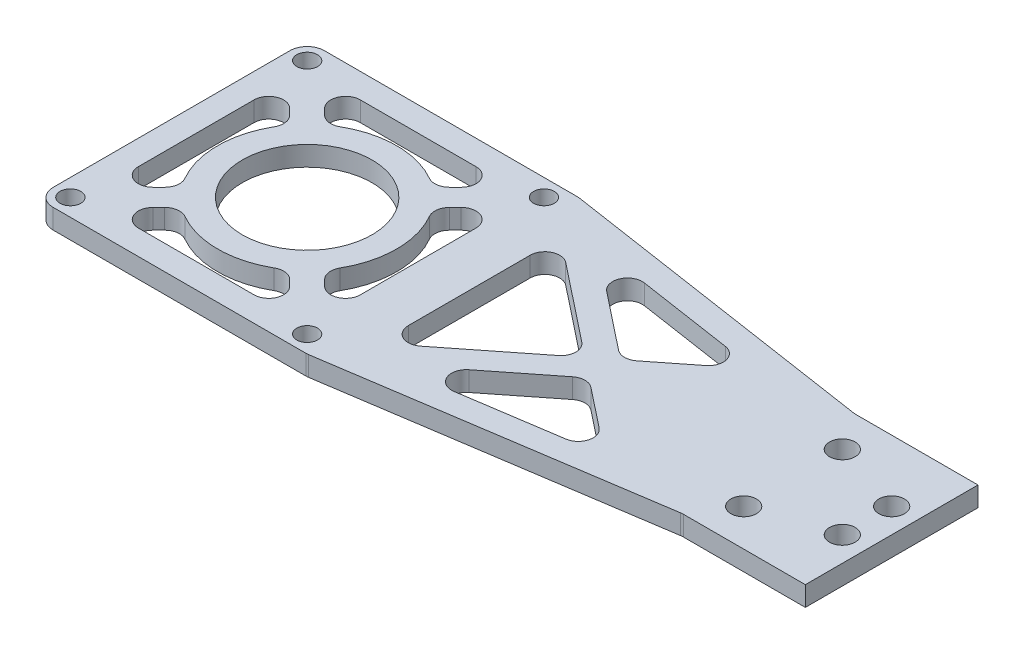
SolidWorks part; units mm, degrees
material "1060 合金"
ref_plane "前视基准面" through (0, 0, 0) normal (0, 0, 1) x (1, 0, 0)
ref_plane "上视基准面" through (0, 0, 0) normal (0, 1, 0) x (1, 0, 0)
ref_plane "右视基准面" through (0, 0, 0) normal (1, 0, 0) x (0, 0, -1)
sketch "草图1" plane through (0, 0, 0) normal (0, 1, 0) x (1, 0, 0)
  line L0 (0, 0) -> (7.5, 0)
  line L1 (-7.5, -10) -> (7.5, -10)
  line L2 (-7.5, -10) -> (-7.5, 10)
  line L3 (-7.5, 10) -> (7.5, 10)
  line L4 (7.5, -10) -> (7.5, 10)
  line L5 (-7.5, -10) -> (7.5, 10) construction
  line L6 (-7.5, 10) -> (7.5, -10) construction
  line L7 (7.5, -5) -> (7.5, 5)
  line L9 (12.5, 17.5) -> (-12.5, 17.5)
  line L10 (12.5, 17.5) -> (12.5, -17.5)
  line L11 (12.5, -17.5) -> (-12.5, -17.5)
  line L12 (-12.5, 17.5) -> (-12.5, -17.5)
  line L13 (12.5, 17.5) -> (-12.5, -17.5) construction
  line L14 (12.5, -17.5) -> (-12.5, 17.5) construction
  circle A0 centre (7.5, 5) radius 2.6
  circle A1 centre (7.5, -5) radius 2.6
  circle A2 centre (-7.5, -10) radius 2.6
  circle A3 centre (-7.5, 10) radius 2.6
  point P0 (0, 0)
  point P11 (7.5, 0)
  dimension "D3" = 10
  dimension "D4" = 5.2
  dimension "D5" = 5.2
  dimension "D6" = 5.2
  dimension "D7" = 5.2
  dimension "D1" = 20
  dimension "D2" = 15
  dimension "D8" = 7.5
  dimension "D9" = 5
extrude "凸台-拉伸1" add sketch "草图1" along normal blind 4
sketch "草图2" plane through (0, 4, 0) normal (0, 1, 0) x (1, 0, 0)
  line L0 (-22.5, 0) -> (0, 0)
  line L1 (-133.482, 27.5) -> (-78.482, 27.5)
  line L2 (-133.482, 27.5) -> (-133.482, -27.5)
  line L3 (-133.482, -27.5) -> (-78.482, -27.5)
  line L4 (-78.482, 27.5) -> (-78.482, -27.5)
  line L5 (-133.482, 27.5) -> (-78.482, -27.5) construction
  line L6 (-133.482, -27.5) -> (-78.482, 27.5) construction
  line L7 (-12.5, 17.5) -> (-12.5, -17.5) construction
  line L8 (-105.982, 0) -> (-22.5, 0)
  line L9 (-78.482, 27.5) -> (-12.5, 17.5)
  line L10 (-12.5, 17.5) -> (-12.5, -17.5)
  line L11 (-12.5, -17.5) -> (-78.482, -27.5)
  circle A0 centre (-22.5, 0) radius 6.0415
  circle A2 centre (-105.982, 0) radius 27.5
  circle A3 centre (-7.5, -10) radius 2.6 construction
  dimension "D1" = 12.0829
  dimension "D2" = 83.482
  dimension "D3" = 15
  dimension "D4" = 55
  dimension "D7" = 90
  dimension "D5" = 55
  dimension "D6" = 55
  dimension "D8" = 180
extrude "凸台-拉伸2" add sketch "草图2" against normal blind 4 separate body
combine bodies "组合1" operation type add bodies to combine 106 107
fillet "圆角1" radius 3.5 6 edges at (-12.5, 2, -17.5) (-78.482, 2, -27.5) (-133.482, 2, 27.5) (-78.482, 2, 27.5) (-12.5, 2, 17.5) (-133.482, 2, -27.5)
sketch "草图3" plane through (0, 4, 0) normal (0, 1, 0) x (1, 0, 0)
  line L0 (-129.982, 24) -> (-105.982, 0)
  line L1 (-105.982, 0) -> (-129.982, -24)
  line L2 (-133.482, 24) -> (-133.482, -24) construction
  circle A0 centre (-105.982, 0) radius 13.15
  dimension "D1" = 90
  dimension "D4" = 26.3
  dimension "D2" = 45
  dimension "D3" = 0
extrude "切除-拉伸1" cut sketch "草图3" against normal blind 10 contours L0 A0 L1 | L1 A0 L0
sketch "草图4" plane through (0, 4, 0) normal (0, 1, 0) x (1, 0, 0)
  line L0 (-93.6076, 12.3744) -> (-105.982, 0)
  line L2 (-133.482, 24) -> (-133.482, -24) construction
  line L4 (-129.982, 24) -> (-81.982, 24)
  line L5 (-129.982, 24) -> (-129.982, -24)
  line L6 (-129.982, -24) -> (-81.982, -24)
  line L7 (-81.982, 24) -> (-81.982, -24)
  line L8 (-129.982, 24) -> (-81.982, -24) construction
  line L9 (-129.982, -24) -> (-81.982, 24) construction
  circle A0 centre (-105.982, 0) radius 17.5
  circle A1 centre (-93.6076, 12.3744) radius 2.1
  circle A2 centre (-81.982, 24) radius 2.1
  dimension "D1" = 35
  dimension "D2" = 4.2
  dimension "D6" = 4.2
  dimension "D3" = 45
  dimension "D4" = 48
  dimension "D5" = 48
extrude "切除-拉伸2" cut sketch "草图4" against normal blind 10 contours L4 A2 L7 | L7 A2 L4
pattern_circular "阵列(圆周)1" count 4 over 360 about axis through (-105.982, 0, 0) along (0, 1, 0) of "切除-拉伸2"
sketch "草图5" plane through (0, 4, 0) normal (0, 1, 0) x (1, 0, 0)
  line L0 (-129.982, 24) -> (-81.982, -24)
  line L1 (-81.982, -24) -> (-81.982, 24)
  line L2 (-81.982, 24) -> (-129.982, -24)
  line L3 (-129.982, -24) -> (-129.982, 24)
  line L20 (-13.51, 12.596) -> (-78.8587, 22.5)
  line L21 (-78.8587, 22.5) -> (-128.482, 22.5)
  line L22 (-128.482, 22.5) -> (-128.482, -22.5)
  line L23 (-128.482, -22.5) -> (-78.8587, -22.5)
  line L24 (-78.8587, -22.5) -> (-13.51, -12.596)
  line L25 (-12.2363, -12.5) -> (7.5, -12.5)
  line L26 (7.5, -12.5) -> (7.5, 12.5)
  line L27 (7.5, 12.5) -> (-12.2363, 12.5)
  line L28 (-13.51, 12.596) -> (-78.8587, 22.5)
  line L29 (-78.8587, 22.5) -> (-128.482, 22.5)
  line L30 (-128.482, 22.5) -> (-128.482, -22.5)
  line L31 (-128.482, -22.5) -> (-78.8587, -22.5)
  line L32 (-78.8587, -22.5) -> (-13.51, -12.596)
  line L33 (-12.2363, -12.5) -> (7.5, -12.5)
  line L34 (7.5, -12.5) -> (7.5, 12.5)
  line L35 (7.5, 12.5) -> (-12.2363, 12.5)
  line L36 (-131.7498, 22.2322) -> (-83.7498, -25.7678)
  line L37 (-83.7498, 25.7678) -> (-131.7498, -22.2322)
  arc A12 (-12.2363, -12.5) -> (-13.51, -12.596) centre (-12.2363, -21) ccw
  arc A13 (-13.51, 12.596) -> (-12.2363, 12.5) centre (-12.2363, 21) ccw
  arc A14 (-12.2363, -12.5) -> (-13.51, -12.596) centre (-12.2363, -21) ccw
  arc A15 (-13.51, 12.596) -> (-12.2363, 12.5) centre (-12.2363, 21) ccw
  circle A18 centre (-105.982, 0) radius 18.15
  circle A19 centre (-105.982, 0) radius 18.15
  dimension "D1" = 5
  dimension "D2" = 5
  dimension "D3" = 2.5
extrude "切除-拉伸3" cut sketch "草图5" against normal blind 10 contours A19 L36 L30 L37
fillet "圆角2" radius 3 4 edges at (-120.4614, 2, 10.9439) (-128.482, 2, 18.9645) (-120.4614, 2, -10.9439) (-128.482, 2, -18.9645)
pattern_circular "阵列(圆周)2" count 4 over 360 about axis through (-105.982, 0, 0) along (0, 1, 0) of "圆角2", "切除-拉伸3"
sketch "草图6" plane through (0, 4, 0) normal (0, 1, 0) x (1, 0, 0)
  line L7 (0, 0) -> (-22.5, 0)
  line L8 (-12.7607, 17.5395) -> (-27.6594, 8.5663)
  line L9 (-12.2363, -17.5) -> (-27.5116, -8.6536)
  line L10 (-78.2213, -27.4605) -> (-78.2213, 27.4605)
  line L11 (-73.2213, -27.4605) -> (-73.2213, 27.4605)
  line L12 (-15.3404, 21.8227) -> (-30.239, 12.8494)
  line L15 (-78.9705, 22.5169) -> (-13.51, 12.596)
  line L16 (-78.9705, 22.5169) -> (-13.51, 12.596)
  line L17 (-14.7421, -21.8268) -> (-30.0174, -12.9803)
  line L18 (-13.51, -12.596) -> (-78.9705, -22.5169)
  line L19 (-13.51, -12.596) -> (-78.9705, -22.5169)
  line L20 (-73.2213, -21.6456) -> (-27.2119, 14.6726)
  line L21 (-27.1195, -14.6586) -> (-73.2213, 21.8227)
  line L22 (-25.5682, -12.6981) -> (-71.6699, 23.7831)
  line L23 (-71.6723, -23.6079) -> (-25.663, 12.7103)
  line L24 (-28.6709, -16.619) -> (-74.7726, 19.8622)
  line L25 (-74.7702, -19.6833) -> (-28.7609, 16.6349)
  circle A0 centre (-22.5, 0) radius 10
  circle A1 centre (-7.5, 10) radius 2.6 construction
  circle A2 centre (-22.5, 0) radius 15
  dimension "D1" = 20
  dimension "D2" = 15
  dimension "D3" = 5
  dimension "D4" = 5
  dimension "D5" = 5
  dimension "D6" = 5
  dimension "D7" = 5
  dimension "D8" = 5
  dimension "D9" = 2.5
  dimension "D10" = 2.5
extrude "切除-拉伸4" cut sketch "草图6" against normal blind 10 contours L11 L25 L24 | L22 L25 L16 | L19 L24 L23
fillet "圆角3" radius 3 9 edges at (-68.2276, 2, 20.8888) (-45.7236, 2, 3.1249) (-30.5007, 2, 15.171) (-30.5969, 2, -15.1856) (-45.7197, 2, -3.2482) (-67.9613, 2, -20.8484) (-49.7535, 2, -0.0641) (-73.2213, 2, 18.4606) (-73.2213, 2, -18.6346)
